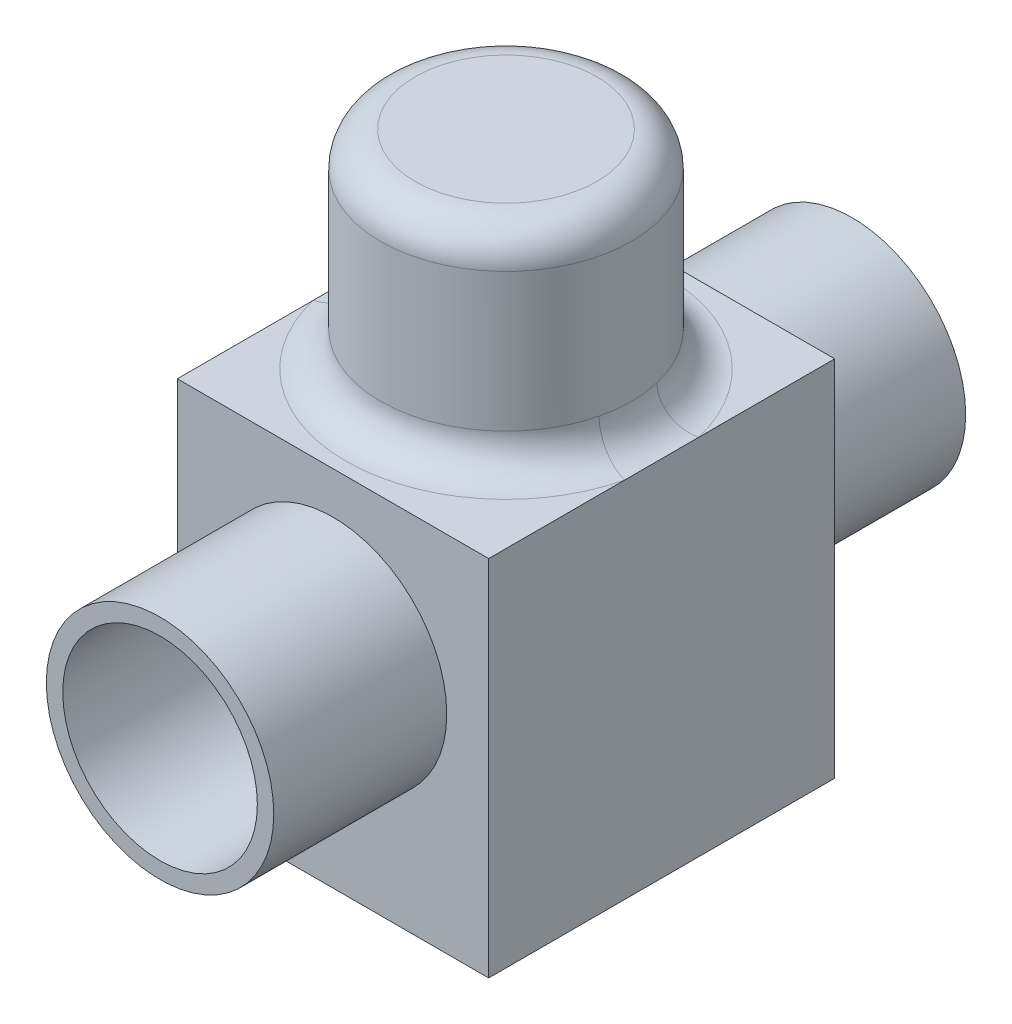
SolidWorks part; units mm, degrees
ref_plane "Front Plane" through (0, 0, 0) normal (0, 0, 1) x (1, 0, 0)
ref_plane "Top Plane" through (0, 0, 0) normal (0, 1, 0) x (1, 0, 0)
ref_plane "Right Plane" through (0, 0, 0) normal (1, 0, 0) x (0, 0, -1)
sketch "Sketch1" plane through (0, 0, 0) normal (0, 1, 0) x (1, 0, 0)
  line L1 (-9, 10) -> (9, 10)
  line L2 (-9, 10) -> (-9, -10)
  line L3 (-9, -10) -> (9, -10)
  line L4 (9, 10) -> (9, -10)
  line L5 (-9, 10) -> (9, -10) construction
  line L6 (-9, -10) -> (9, 10) construction
  point P0 (0, 0)
  dimension "D1" = 18
  dimension "D2" = 20
extrude "Boss-Extrude1" add sketch "Sketch1" along normal blind 18
sketch "Sketch2" plane through (0, 0, 10) normal (0, 0, 1) x (1, 0, 0)
  line L0 (-9, 0) -> (9, 0) construction
  line L1 (9, 18) -> (9, 0) construction
  circle A0 centre (0, 9) radius 5.625
  circle A1 centre (0, 9) radius 6.575
  dimension "D1" = 11.25
  dimension "D2" = 13.15
  dimension "D3" = 9
  dimension "D4" = 9
sketch "Sketch3" plane through (0, 0, -10) normal (0, 0, -1) x (-1, 0, 0)
  line L0 (-9, 0) -> (9, 0) construction
  circle A0 centre (0, 9) radius 5.625
  circle A1 centre (0, 9) radius 6.575
  dimension "D2" = 11.25
  dimension "D3" = 13.15
  dimension "D1" = 9
sketch "Sketch6" plane through (0, 18, 0) normal (0, 1, 0) x (1, 0, 0)
  circle A0 centre (0, 0) radius 7.25
  dimension "D1" = 14.5
extrude "Boss-Extrude4" add sketch "Sketch6" along normal blind 12
fillet "Fillet1" radius 2 2 edges at (0, 30, 7.25) (0, 18, 7.25)
extrude "Boss-Extrude5" add sketch "Sketch2" along normal blind 10
extrude "Boss-Extrude6" add sketch "Sketch3" along normal blind 10
sketch "Sketch7" plane through (0, 0, -10) normal (0, 0, -1) x (-1, 0, 0)
  circle A0 centre (0, 9) radius 5.625
extrude "Cut-Extrude2" cut sketch "Sketch7" against normal blind 41
sketch "Sketch8" plane through (0, 0, 0) normal (0, -1, 0) x (1, 0, 0)
  line L0 (9, 10) -> (9, -10) construction
  line L1 (-9, 10) -> (9, 10)
  line L2 (-9, 10) -> (-9, -10)
  line L3 (-9, -10) -> (9, -10)
  line L4 (9, 10) -> (9, -10)
extrude "Boss-Extrude7" add sketch "Sketch8" along normal blind 3
